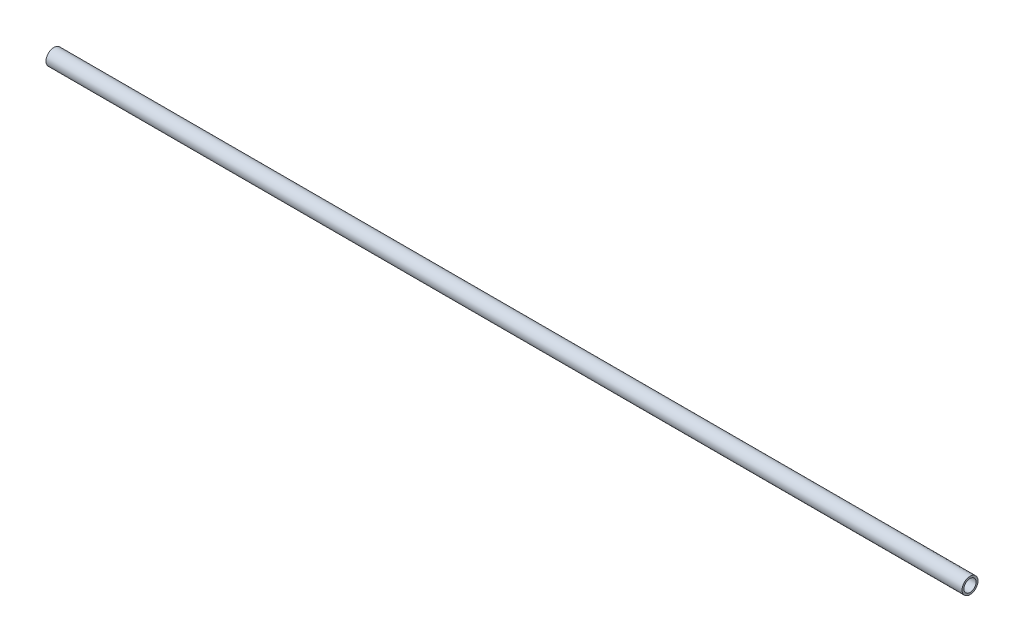
SolidWorks part; units mm, degrees
material "AISI 1010 Steel, hot rolled bar"
ref_plane "Front Plane" through (0, 0, 0) normal (0, 0, 1) x (1, 0, 0)
ref_plane "Top Plane" through (0, 0, 0) normal (0, 1, 0) x (1, 0, 0)
ref_plane "Right Plane" through (0, 0, 0) normal (1, 0, 0) x (0, 0, -1)
sketch "Sketch1" plane through (0, 0, 0) normal (1, 0, 0) x (0, 0, -1)
  circle A0 centre (0, 0) radius 12.7
  circle A1 centre (0, 0) radius 9.652
  dimension "D1" = 25.4
  dimension "D2" = 19.304
extrude "Boss-Extrude1" add sketch "Sketch1" along normal blind 1460.5
